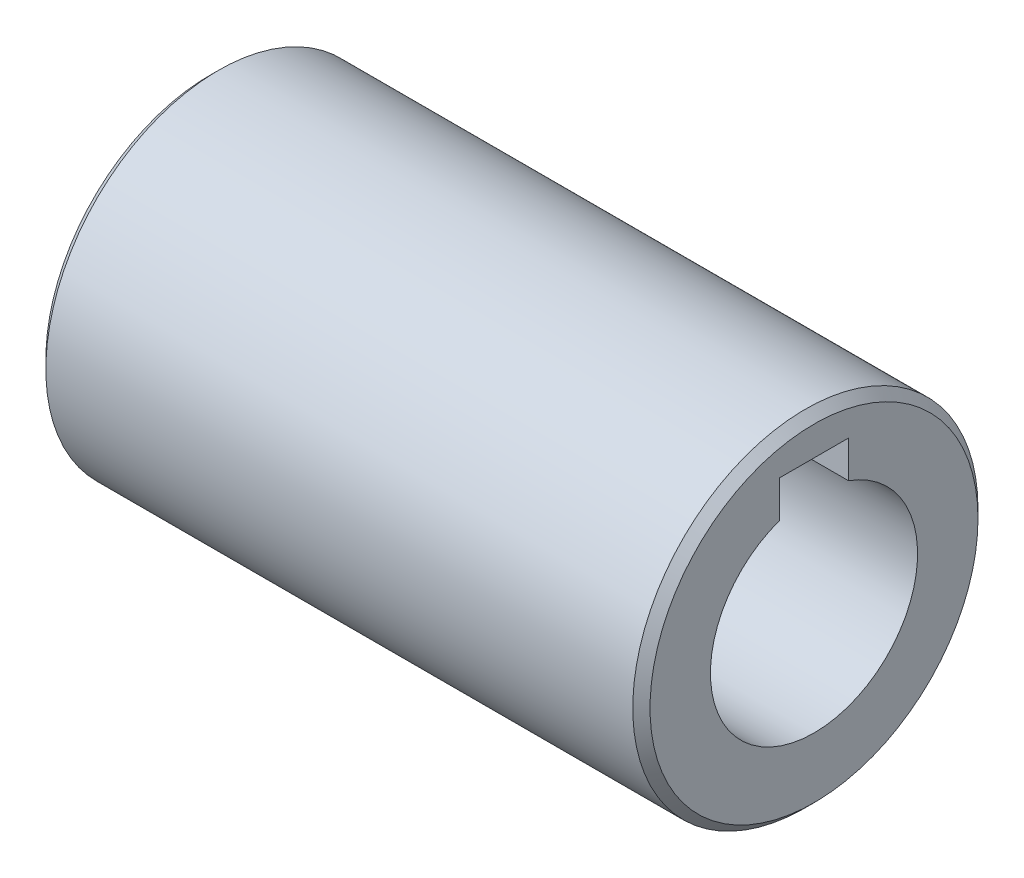
SolidWorks part; units mm, degrees
material "Alliage 1060"
ref_plane "Plan de face" through (0, 0, 0) normal (0, 0, 1) x (1, 0, 0)
ref_plane "Plan de dessus" through (0, 0, 0) normal (0, 1, 0) x (1, 0, 0)
ref_plane "Plan de droite" through (0, 0, 0) normal (1, 0, 0) x (0, 0, -1)
sketch "Esquisse1" plane through (0, 0, 0) normal (1, 0, 0) x (0, 0, -1)
  circle A0 centre (0, 0) radius 6
  circle A1 centre (0, 0) radius 10
  dimension "D1" = 12
  dimension "D2" = 20
extrude "Boss.-Extru.1" add sketch "Esquisse1" along normal blind 35
sketch "Esquisse2" plane through (0, 0, 0) normal (-1, 0, 0) x (0, 0, 1)
  line L0 (0, 14.1431) -> (0, -15.0016) construction
  line L1 (-7.1335, 6) -> (7.6519, 6) construction
  line L2 (-2, 7.8) -> (2, 7.8)
  line L3 (-2, 7.8) -> (-2, 1.7354)
  line L4 (-2, 1.7354) -> (2, 1.7354)
  line L5 (2, 7.8) -> (2, 1.7354)
  circle A0 centre (0, 0) radius 6 construction
  dimension "D1" = 4
  dimension "D2" = 1.8
extrude "Enlèv. mat.-Extru.1" cut sketch "Esquisse2" against normal through all
chamfer "Chanfrein1" distance 0.5 angle 45 2 edges at (0, 0, -10) (35, 0, -10)
